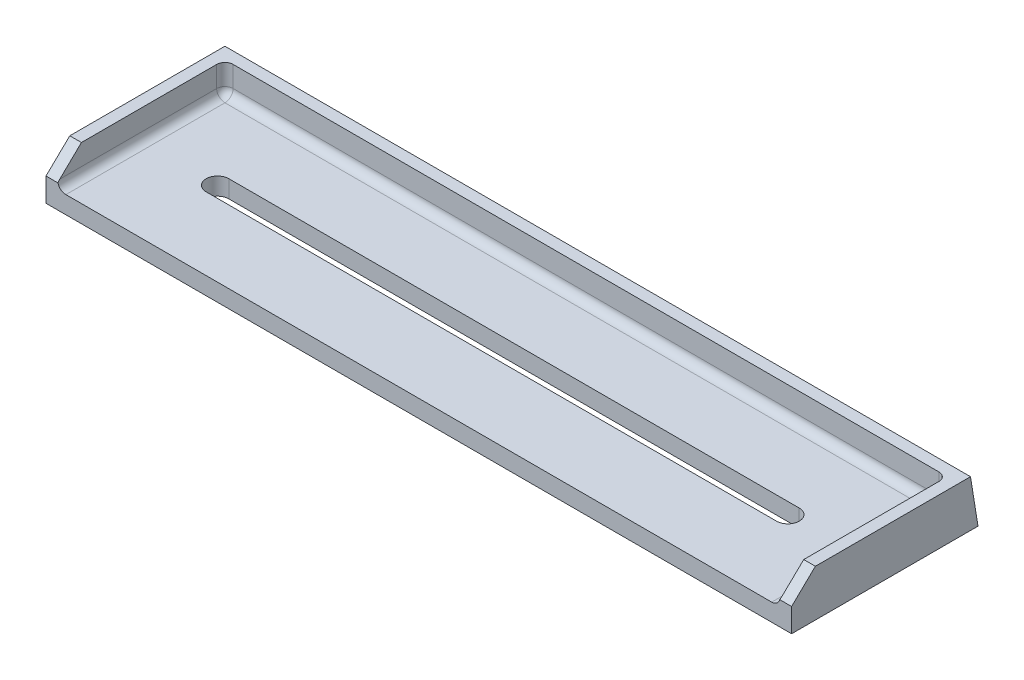
SolidWorks part; units mm, degrees
material "6061-T6 (SS)"
ref_plane "Front Plane" through (0, 0, 0) normal (0, 0, 1) x (1, 0, 0)
ref_plane "Top Plane" through (0, 0, 0) normal (0, 1, 0) x (1, 0, 0)
ref_plane "Right Plane" through (0, 0, 0) normal (1, 0, 0) x (0, 0, -1)
sketch "Sketch1" plane through (0, 0, 0) normal (0, 1, 0) x (1, 0, 0)
  line L1 (50.8, -12.7) -> (-50.8, -12.7)
  line L2 (50.8, -12.7) -> (50.8, 12.7)
  line L3 (50.8, 12.7) -> (-50.8, 12.7)
  line L4 (-50.8, -12.7) -> (-50.8, 12.7)
  line L5 (50.8, -12.7) -> (-50.8, 12.7) construction
  line L6 (50.8, 12.7) -> (-50.8, -12.7) construction
  point P0 (0, 0)
  dimension "D1" = 101.6
  dimension "D2" = 25.4
extrude "Boss-Extrude1" add sketch "Sketch1" along normal blind 6.35
sketch "Sketch2" plane through (-50.8, 0, 0) normal (-1, 0, 0) x (0, 0, 1)
  line L0 (-12.7, 0) -> (-11.6789, 6.35)
  line L1 (-12.7, 6.35) -> (12.7, 6.35) construction
  line L2 (-11.6789, 6.35) -> (-12.7, 6.35)
  line L3 (-12.7, 6.35) -> (-12.7, 0)
  dimension "D1" = 1.0211
extrude "Cut-Extrude2" cut sketch "Sketch2" against normal blind 101.6
sketch "Sketch4" plane through (0, 6.35, 0) normal (0, 1, 0) x (1, 0, 0)
  line L0 (-50.8, -12.7) -> (50.8, -12.7) construction
  line L1 (-49.2125, -12.7) -> (49.2125, -12.7)
  line L2 (-49.2125, -12.7) -> (-49.2125, 10.0914)
  line L3 (-49.2125, 10.0914) -> (49.2125, 10.0914)
  line L4 (49.2125, -12.7) -> (49.2125, 10.0914)
  line L5 (-50.8, 11.6789) -> (-50.8, -12.7) construction
  line L6 (50.8, -12.7) -> (50.8, 11.6789) construction
  line L7 (50.8, 11.6789) -> (-50.8, 11.6789) construction
  dimension "D1" = 1.5875
  dimension "D2" = 1.5875
  dimension "D3" = 1.5875
extrude "Cut-Extrude3" cut sketch "Sketch4" against normal blind 3.9675
sketch "Sketch5" plane through (0, 2.3825, 0) normal (0, 1, 0) x (1, 0, 0)
  line L0 (-49.2125, 10.0914) -> (-49.2125, -12.7) construction
  line L1 (-49.2125, -12.7) -> (49.2125, -12.7) construction
  line L2 (49.2125, -12.7) -> (49.2125, 10.0914) construction
  line L3 (-38.862, -2.8187) -> (38.862, -2.8187)
  line L4 (-38.862, 0.2787) -> (38.862, 0.2787)
  arc A0 (-38.862, 0.2787) -> (-38.862, -2.8187) centre (-38.862, -1.27) ccw
  arc A1 (38.862, -2.8187) -> (38.862, 0.2787) centre (38.862, -1.27) ccw
  dimension "D1" = 10.3505
  dimension "D2" = 11.43
  dimension "D3" = 10.3505
  dimension "D4" = 11.43
extrude "Cut-Extrude6" cut sketch "Sketch5" against normal blind 2.54
sketch "Sketch6" plane through (-49.2125, 0, 0) normal (1, 0, 0) x (0, 0, -1)
  line L0 (-9.459, 6.35) -> (-12.7, 3.2233)
  line L1 (10.0914, 6.35) -> (-12.7, 6.35) construction
  line L2 (-12.7, 2.3825) -> (-12.7, 6.35) construction
  line L3 (-9.459, 6.35) -> (-12.7, 6.35)
  line L4 (-12.7, 6.35) -> (-12.7, 3.2233)
  dimension "D1" = 3.1267
  dimension "D2" = 3.241
extrude "Cut-Extrude7" cut sketch "Sketch6" against normal blind 1.5875
sketch "Sketch7" plane through (49.2125, 0, 0) normal (-1, 0, 0) x (0, 0, 1)
  line L0 (9.459, 6.35) -> (12.7, 3.2233)
  line L1 (12.7, 6.35) -> (-10.0914, 6.35) construction
  line L2 (12.7, 2.3825) -> (12.7, 6.35) construction
  line L3 (9.459, 6.35) -> (12.7, 6.35)
  line L4 (12.7, 6.35) -> (12.7, 3.2233)
  dimension "D1" = 3.241
  dimension "D2" = 3.1267
extrude "Cut-Extrude8" cut sketch "Sketch7" against normal blind 1.5875
fillet "Fillet1" radius 1.1227 5 edges at (49.2125, 4.3663, -10.0914) (49.2125, 2.3825, 1.3043) (-49.2125, 4.3663, -10.0914) (-49.2125, 2.3825, 1.3043) (0, 2.3825, -10.0914)
